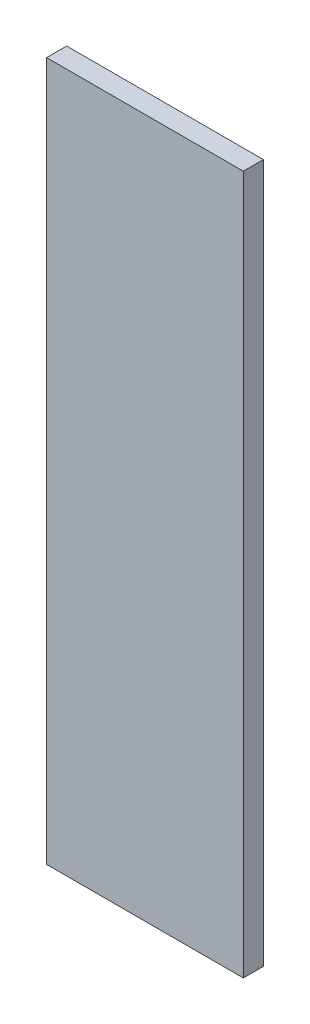
SolidWorks part; units mm, degrees
ref_plane "Front Plane" through (0, 0, 0) normal (0, 0, 1) x (1, 0, 0)
ref_plane "Top Plane" through (0, 0, 0) normal (0, 1, 0) x (1, 0, 0)
ref_plane "Right Plane" through (0, 0, 0) normal (1, 0, 0) x (0, 0, -1)
sketch "Sketch1" plane through (0, 0, 0) normal (0, 0, 1) x (1, 0, 0)
  line L4 (0.24, 0.87) -> (-0.25, 0.87)
  line L5 (0.24, -0.87) -> (0.24, 0.87)
  line L6 (-0.25, -0.87) -> (0.24, -0.87)
  line L7 (-0.25, 0.87) -> (-0.25, -0.87)
  line L8 (0.24, 0.87) -> (-0.25, 0.87)
  line L9 (0.24, -0.87) -> (0.24, 0.87)
  line L10 (-0.25, -0.87) -> (0.24, -0.87)
  line L11 (-0.25, 0.87) -> (-0.25, -0.87)
  dimension "D1" = 0
extrude "Boss-Extrude1" add sketch "Sketch1" against normal up to surface (0.05 mm away)
